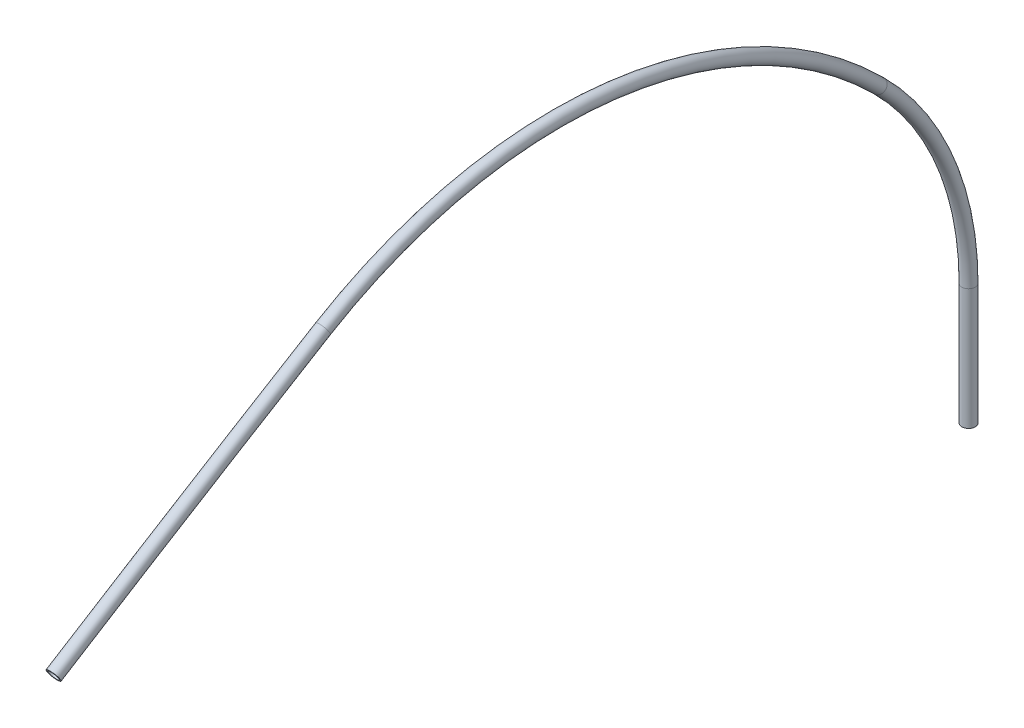
SolidWorks part; units mm, degrees
ref_plane "Alzado" through (0, 0, 0) normal (0, 0, 1) x (1, 0, 0)
ref_plane "Planta" through (0, 0, 0) normal (0, 1, 0) x (1, 0, 0)
ref_plane "Vista lateral" through (0, 0, 0) normal (1, 0, 0) x (0, 0, -1)
sketch "Croquis5" plane through (0, 0, 0) normal (1, 0, 0) x (0, 0, -1)
  line L0 (-12, 40) -> (-12, 130.5607)
  arc A0 (-12, 130.5607) -> (-79.0838, 292.1382) centre (-240.129, 130.5607) ccw
  arc A1 (-79.0838, 292.1382) -> (-495.1068, 342.6772) centre (-319.4631, 50.9644) ccw
  arc A2 (-495.1068, 342.6772) -> (-696.7767, 218.7723) centre (6313.7898, -10965.6895) ccw
  dimension "D1" = 40
ref_plane "Plano1" through (0, 40, 12) normal (0, 1, 0) x (-1, 0, 0)
sketch "Croquis7" plane through (0, 40, 12) normal (0, 1, 0) x (-1, 0, 0)
  circle A0 centre (0, 0) radius 5
  dimension "D1" = 10
sweep "Barrer1" add profiles "Croquis7" path "Croquis5"
shell "Vaciado2" thickness 1
